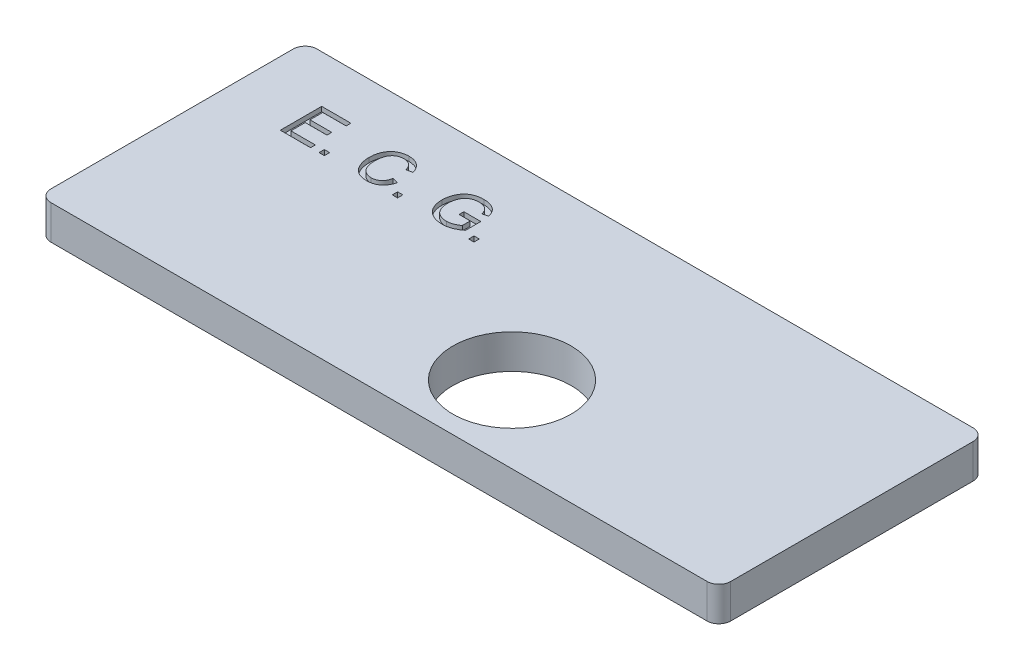
SolidWorks part; units mm, degrees
material "ABS"
ref_plane "Front Plane" through (0, 0, 0) normal (0, 0, 1) x (1, 0, 0)
ref_plane "Top Plane" through (0, 0, 0) normal (0, 1, 0) x (1, 0, 0)
ref_plane "Right Plane" through (0, 0, 0) normal (1, 0, 0) x (0, 0, -1)
sketch "Sketch1" plane through (0, 0, 0) normal (0, 1, 0) x (1, 0, 0)
  line L1 (1, 0) -> (56.5, 0)
  line L2 (0, 1) -> (0, 21.5)
  line L3 (1, 22.5) -> (56.5, 22.5)
  line L4 (57.5, 1) -> (57.5, 21.5)
  arc A0 (56.5, 22.5) -> (57.5, 21.5) centre (56.5, 21.5) cw
  arc A1 (57.5, 1) -> (56.5, 0) centre (56.5, 1) cw
  arc A2 (1, 0) -> (0, 1) centre (1, 1) cw
  arc A3 (0, 21.5) -> (1, 22.5) centre (1, 21.5) cw
  point P11 (0, 0)
  dimension "D1" = 1
extrude "Boss-Extrude1" add sketch "Sketch1" along normal blind 2.9
sketch "Sketch2" plane through (0, 0, 0) normal (0, 1, 0) x (1, 0, 0)
  line L0 (0, 0) -> (0, 1.5)
  line L1 (0, 21.5) -> (0, 1) construction
  line L2 (0, 1.5) -> (1.5, 1.5)
  line L3 (1.5, 1.5) -> (33.5, 1.5)
  line L4 (33.5, 1.5) -> (33.5, 6.5)
  circle A0 centre (33.5, 6.5) radius 5
extrude "Cut-Extrude1" cut sketch "Sketch2" along normal blind 10
ref_plane "Plane1" through (0, 3, 0) normal (0, 1, 0) x (1, 0, 0)
sketch "Sketch3" plane through (0, 3, 0) normal (0, 1, 0) x (1, 0, 0)
  text T0 "E. C. G."
  point P1 (0, 0)
extrude "Cut-Extrude2" cut sketch "Sketch3" against normal blind 0.5
